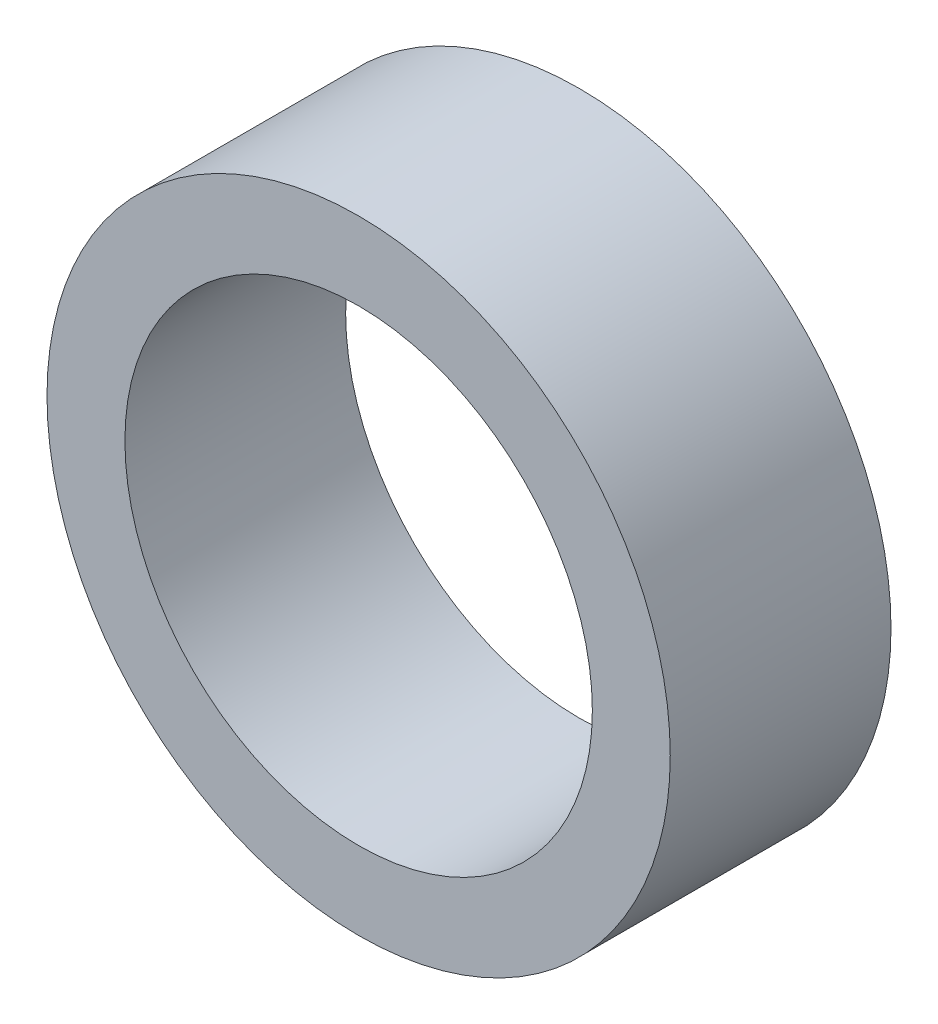
SolidWorks part; units mm, degrees
material "Bronze"
ref_plane "Piano frontale" through (0, 0, 0) normal (0, 0, 1) x (1, 0, 0)
ref_plane "Piano superiore" through (0, 0, 0) normal (0, 1, 0) x (1, 0, 0)
ref_plane "Piano destro" through (0, 0, 0) normal (1, 0, 0) x (0, 0, -1)
sketch "Sketch1" plane through (0, 0, 0) normal (0, 0, 1) x (1, 0, 0)
  circle A0 centre (0, 0) radius 18
  circle A1 centre (0, 0) radius 24
  dimension "D1" = 36
  dimension "D2" = 48
extrude "Extrude1" add sketch "Sketch1" along normal mid plane 17
